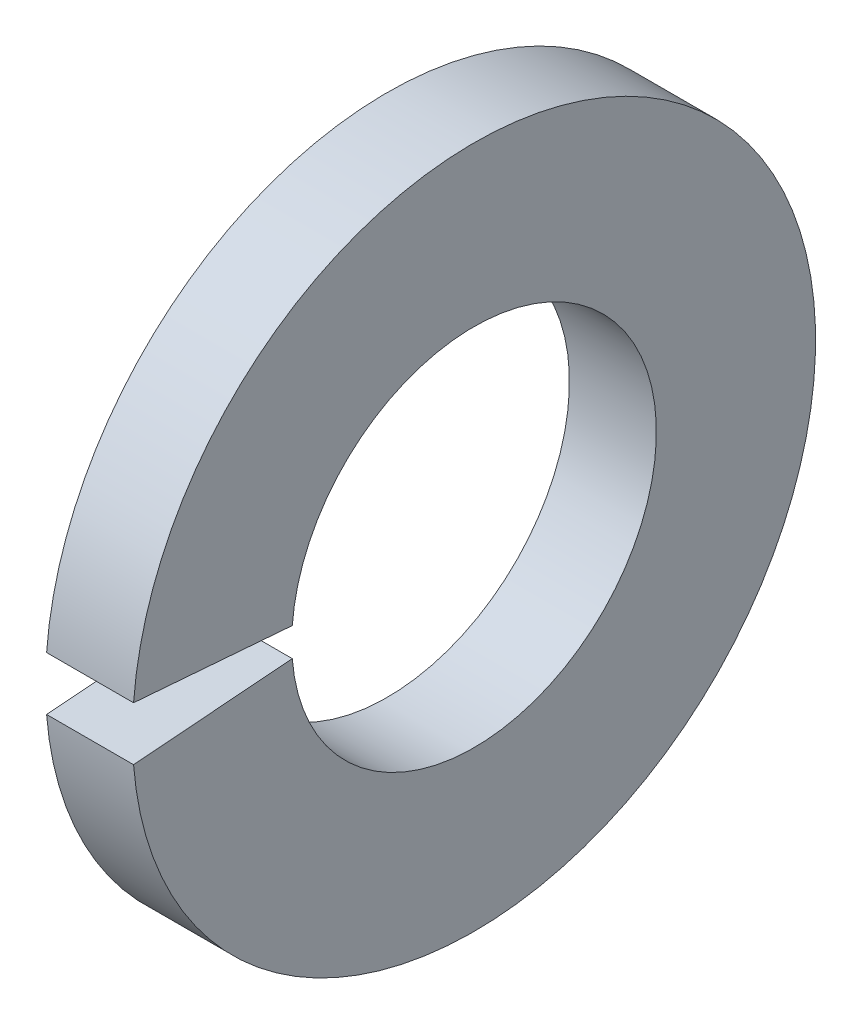
SolidWorks part; units mm, degrees
material "Chrome Stainless Steel"
ref_plane "Front Plane" through (0, 0, 0) normal (0, 0, 1) x (1, 0, 0)
ref_plane "Top Plane" through (0, 0, 0) normal (0, 1, 0) x (1, 0, 0)
ref_plane "Right Plane" through (0, 0, 0) normal (1, 0, 0) x (0, 0, -1)
ref_plane "Plane1" through (0, 0, 0) normal (0, 0.9969, 0.0785) x (-1, 0, 0)
sketch "Sketch1" plane through (0, 0, 0) normal (0, 0.9969, 0.0785) x (-1, 0, 0)
  line L0 (1.5748, 6.1849) -> (0, 6.1849)
  line L1 (0, 6.1849) -> (0, 3.302)
  line L2 (0, 3.302) -> (1.5748, 3.302)
  line L3 (1.5748, 3.302) -> (1.5748, 6.1849)
  line L4 (0, 0) -> (1.5748, 0) construction
revolve "Revolve1" add sketch "Sketch1" angle 351 about L4
